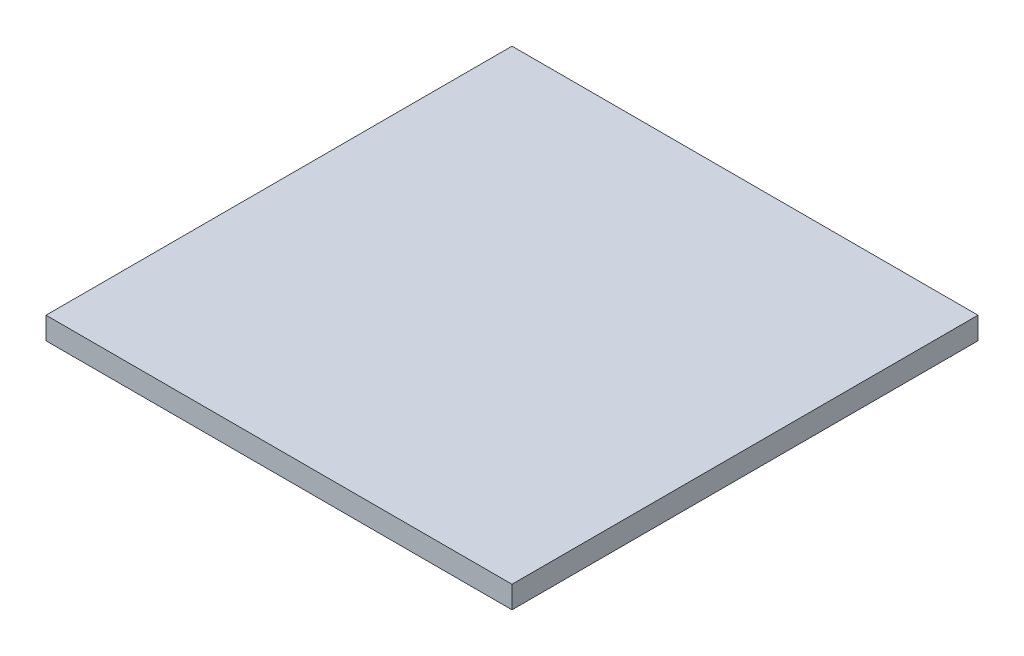
SolidWorks part; units mm, degrees
ref_plane "Front Plane" through (0, 0, 0) normal (0, 0, 1) x (1, 0, 0)
ref_plane "Top Plane" through (0, 0, 0) normal (0, 1, 0) x (1, 0, 0)
ref_plane "Right Plane" through (0, 0, 0) normal (1, 0, 0) x (0, 0, -1)
sketch "Sketch1" plane through (0, 0, 0) normal (0, 1, 0) x (1, 0, 0)
  line L1 (0, 0) -> (42, 0)
  line L2 (0, 0) -> (0, -42)
  line L3 (0, -42) -> (42, -42)
  line L4 (42, 0) -> (42, -42)
  dimension "D1" = 42
extrude "Boss-Extrude1" add sketch "Sketch1" along normal blind 2
